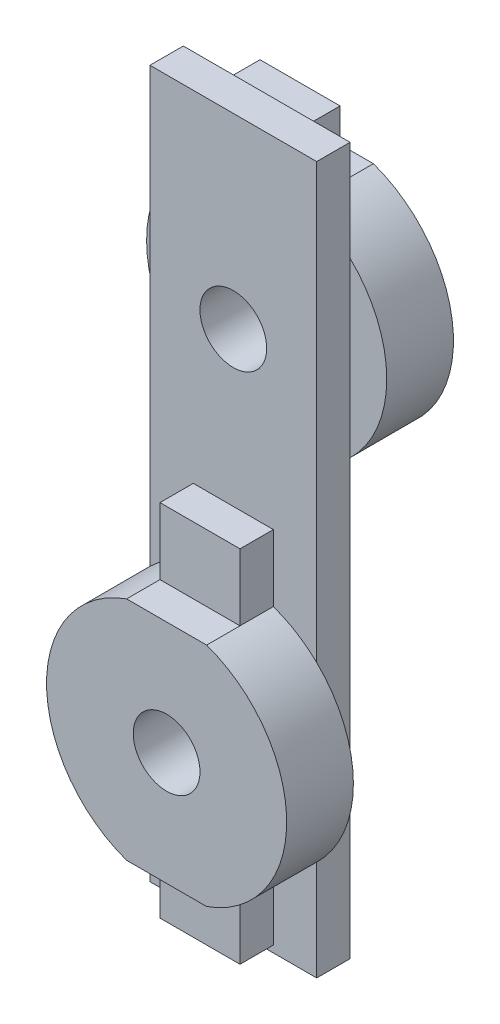
SolidWorks part; units mm, degrees
ref_plane "Front Plane" through (0, 0, 0) normal (0, 0, 1) x (1, 0, 0)
ref_plane "Top Plane" through (0, 0, 0) normal (0, 1, 0) x (1, 0, 0)
ref_plane "Right Plane" through (0, 0, 0) normal (1, 0, 0) x (0, 0, -1)
sketch "Sketch1" plane through (0, 0, 0) normal (0, 0, 1) x (1, 0, 0)
  line L0 (0, 57.9798) -> (0, -61.4774) construction
  line L2 (-12.5, 56) -> (12.5, 56)
  line L3 (-12.5, 56) -> (-12.5, -50)
  line L4 (-12.5, -50) -> (12.5, -50)
  line L5 (12.5, 56) -> (12.5, -50)
  point P3 (0, 0)
  dimension "D1" = 25
  dimension "D2" = 106
extrude "Boss-Extrude1" add sketch "Sketch1" along normal blind 5
sketch "Sketch2" plane through (0, 0, 5) normal (0, 0, 1) x (1, 0, 0)
  line L0 (0, 98.9344) -> (0, -92.324) construction
  line L21 (-12.5, -50) -> (12.5, -50) construction
  line L22 (-6, 4.9706) -> (6, 4.9706)
  line L23 (6, 4.9706) -> (6, -5.0294)
  line L30 (-6, 4.9706) -> (-6, -5.0294)
  line L31 (-6, -38.9706) -> (-6, -48.9706)
  line L32 (-6, -48.9706) -> (6, -48.9706)
  line L33 (6, -48.9706) -> (6, -38.9706)
  circle A8 centre (0, -22) radius 18
  circle A11 centre (0, -22) radius 5
  dimension "D1" = 10
  dimension "D3" = 12
  dimension "D6" = 12
  dimension "D2" = 28
  dimension "D4" = 10
  dimension "D5" = 10
extrude "Boss-Extrude3" add sketch "Sketch2" along normal blind 10
sketch "Sketch4" plane through (0, 0, 0) normal (0, 0, -1) x (-1, 0, 0)
  line L0 (0, 62.4094) -> (0, -67.8669) construction
  line L1 (-12.5, 56) -> (12.5, 56) construction
  line L5 (-6, 44.9706) -> (-6, 54.9706)
  line L6 (-6, 54.9706) -> (6, 54.9706)
  line L7 (6, 54.9706) -> (6, 44.9706)
  line L8 (6, 11.0294) -> (6, 1.0294)
  line L9 (6, 1.0294) -> (-6, 1.0294)
  line L10 (-6, 1.0294) -> (-6, 11.0294)
  circle A0 centre (0, 28) radius 5
  circle A1 centre (0, 28) radius 18
  arc A2 (-6, 11.0294) -> (6, 11.0294) centre (0, 28) cw
  arc A3 (-6, 44.9706) -> (6, 44.9706) centre (0, 28) ccw
  dimension "D1" = 28
  dimension "D2" = 12
  dimension "D3" = 10
  dimension "D4" = 10
  dimension "D5" = 10
  dimension "D6" = 10
extrude "Boss-Extrude4" add sketch "Sketch4" along normal blind 10
sketch "Sketch5" plane through (0, 0, 0) normal (0, 0, -1) x (-1, 0, 0)
  line L1 (12.5, -50) -> (-12.5, -50) construction
  circle A0 centre (0, 28) radius 5
  circle A1 centre (0, -22) radius 5
  dimension "D1" = 10
  dimension "D2" = 10
  dimension "D3" = 50
  dimension "D4" = 28
extrude "Cut-Extrude2" cut sketch "Sketch5" against normal blind 5
sketch "Sketch6" plane through (0, 0, -10) normal (0, 0, -1) x (-1, 0, 0)
  line L0 (-6, 54.9706) -> (6, 54.9706)
  line L1 (6, 54.9706) -> (6, 44.9706)
  line L2 (6, 44.9706) -> (-6, 44.9706)
  line L3 (-6, 44.9706) -> (-6, 54.9706)
  line L4 (-6, 11.0294) -> (6, 11.0294)
  line L5 (6, 11.0294) -> (6, 1.0294)
  line L6 (6, 1.0294) -> (-6, 1.0294)
  line L7 (-6, 1.0294) -> (-6, 11.0294)
extrude "Cut-Extrude3" cut sketch "Sketch6" against normal blind 5
sketch "Sketch7" plane through (0, 0, 15) normal (0, 0, 1) x (1, 0, 0)
  line L0 (-6, 4.9706) -> (6, 4.9706)
  line L1 (6, 4.9706) -> (6, -5.0294)
  line L2 (6, -5.0294) -> (-6, -5.0294)
  line L3 (-6, -5.0294) -> (-6, 4.9706)
  line L4 (-6, -38.9706) -> (6, -38.9706)
  line L5 (6, -38.9706) -> (6, -48.9706)
  line L6 (6, -48.9706) -> (-6, -48.9706)
  line L7 (-6, -48.9706) -> (-6, -38.9706)
extrude "Cut-Extrude4" cut sketch "Sketch7" against normal blind 5
